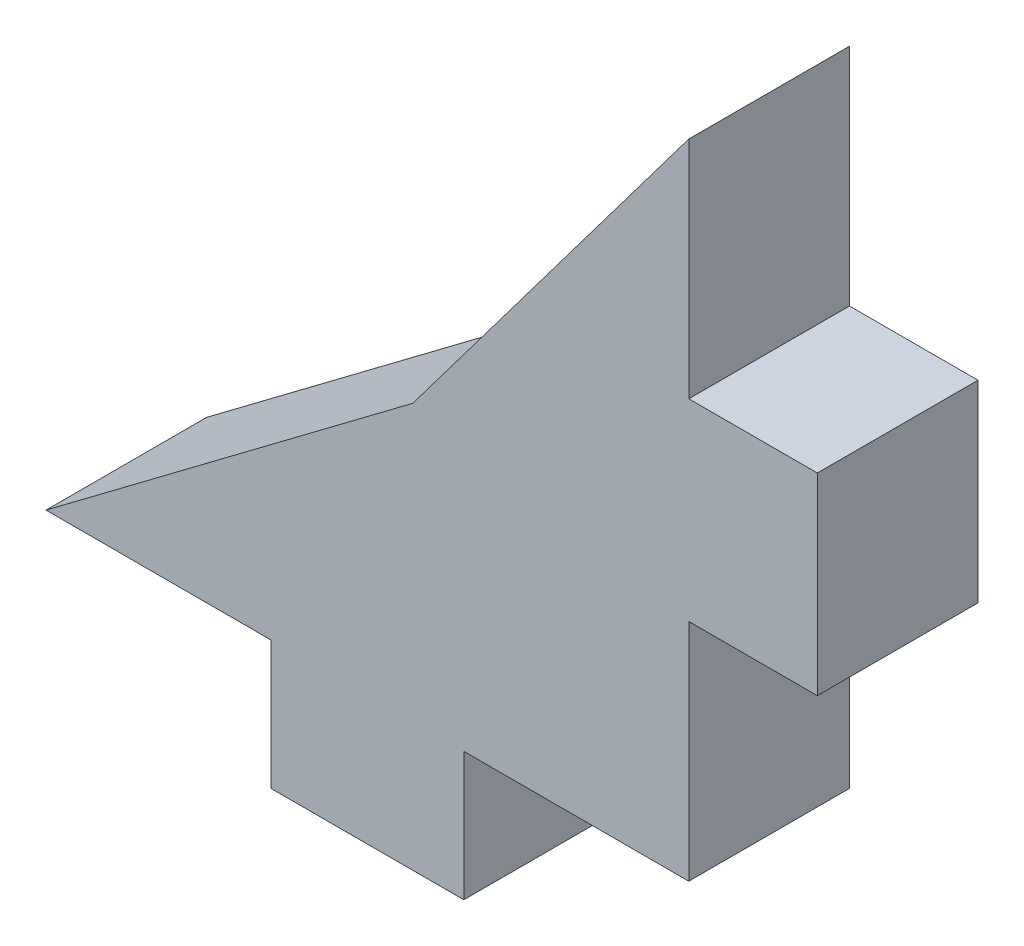
SolidWorks part; units mm, degrees
ref_plane "前视基准面" through (0, 0, 0) normal (0, 0, 1) x (1, 0, 0)
ref_plane "上视基准面" through (0, 0, 0) normal (0, 1, 0) x (1, 0, 0)
ref_plane "右视基准面" through (0, 0, 0) normal (1, 0, 0) x (0, 0, -1)
sketch "草图1" plane through (0, 0, 0) normal (0, 0, 1) x (1, 0, 0)
  line L0 (0, 0) -> (-20, 0)
  line L1 (0, 0) -> (0, 20)
  line L2 (0, 20) -> (-20, 0)
  dimension "D1" = 20
  dimension "D2" = 20
extrude "凸台-拉伸1" add sketch "草图1" along normal blind 5
sketch "草图2" plane through (0, 0, 5) normal (0, 0, 1) x (1, 0, 0)
  line L0 (0, 20) -> (-20, 0) construction
  line L1 (0, 20) -> (-20, 0)
  line L2 (-10, 10) -> (-8.5858, 8.5858)
  line L3 (-8.5858, 8.5858) -> (-20, 0)
  line L4 (-8.5858, 8.5858) -> (0, 20)
  line M2 (0, 20) -> (-20, 0)
  dimension "D1" = 2
extrude "切除-拉伸1" cut sketch "草图2" against normal blind 5 contours L3 L2 L1 | L2 L4 M2
sketch "草图3" plane through (0, 0, 0) normal (0, -1, 0) x (1, 0, 0)
  line L0 (-10, 0) -> (-13, 0)
  line L1 (-20, 0) -> (0, 0) construction
  line L2 (-13, 0) -> (-13, 5)
  line L3 (-20, 5) -> (0, 5) construction
  line L4 (-13, 5) -> (-7, 5)
  line L5 (-7, 5) -> (-7, 0)
  line L6 (-7, 0) -> (-10, 0)
extrude "凸台-拉伸2" add sketch "草图3" along normal blind 5
sketch "草图4" plane through (0, 0, 0) normal (1, 0, 0) x (0, 0, -1)
  line L0 (0, 10) -> (0, 7)
  line L1 (0, 0) -> (0, 20) construction
  line L2 (0, 7) -> (-5, 7)
  line L3 (-5, 0) -> (-5, 20) construction
  line L4 (-5, 7) -> (-5, 13)
  line L5 (-5, 13) -> (0, 13)
  line L6 (0, 13) -> (0, 10)
extrude "凸台-拉伸3" add sketch "草图4" along normal blind 5
sketch "草图5" plane through (0, -5, 0) normal (0, -1, 0) x (1, 0, 0)
  line L4 (-13, 0) -> (-7, 0)
  line L5 (-7, 0) -> (-7, 5)
  line L6 (-7, 5) -> (-13, 5)
  line L7 (-13, 5) -> (-13, 0)
  line L8 (-13, 0) -> (-7, 0)
  line L9 (-7, 0) -> (-7, 5)
  line L10 (-7, 5) -> (-13, 5)
  line L11 (-13, 5) -> (-13, 0)
  dimension "D1" = 0
extrude "切除-拉伸2" cut sketch "草图5" against normal blind 1
sketch "草图6" plane through (5, 0, 0) normal (1, 0, 0) x (0, 0, -1)
  line L4 (0, 7) -> (0, 13)
  line L5 (0, 13) -> (-5, 13)
  line L6 (-5, 13) -> (-5, 7)
  line L7 (-5, 7) -> (0, 7)
  line L8 (0, 7) -> (0, 13)
  line L9 (0, 13) -> (-5, 13)
  line L10 (-5, 13) -> (-5, 7)
  line L11 (-5, 7) -> (0, 7)
  dimension "D1" = 0
extrude "切除-拉伸3" cut sketch "草图6" against normal blind 1
